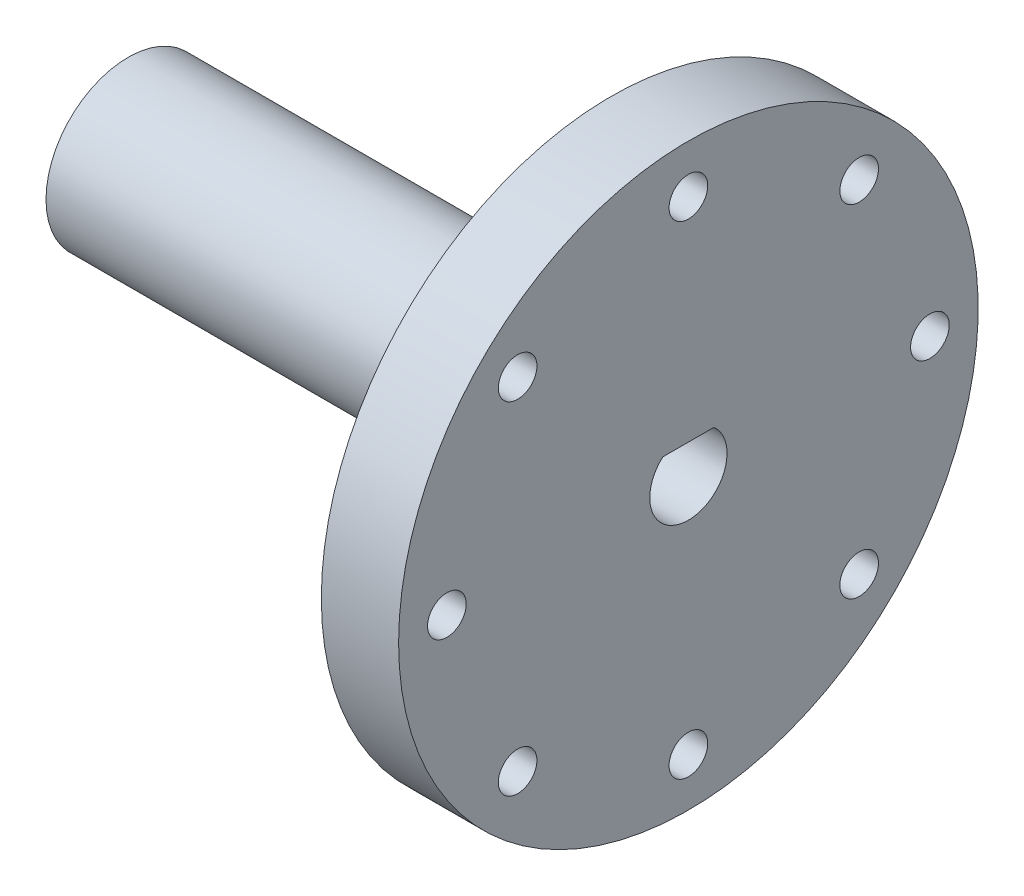
SolidWorks part; units mm, degrees
ref_plane "Front Plane" through (0, 0, 0) normal (0, 0, 1) x (1, 0, 0)
ref_plane "Top Plane" through (0, 0, 0) normal (0, 1, 0) x (1, 0, 0)
ref_plane "Right Plane" through (0, 0, 0) normal (1, 0, 0) x (0, 0, -1)
sketch "Sketch1" plane through (0, 0, 0) normal (0, 0, 1) x (1, 0, 0)
  line L0 (0, 4) -> (58, 4)
  line L1 (58, 4) -> (58, 30)
  line L2 (58, 30) -> (50, 30)
  line L3 (50, 30) -> (50, 8.5)
  line L4 (50, 8.5) -> (0, 8.5)
  line L5 (0, 8.5) -> (0, 4)
  line L6 (0, 0) -> (73.8575, 0) construction
  dimension "D1" = 58
  dimension "D2" = 50
  dimension "D3" = 4
  dimension "D4" = 8.5
  dimension "D5" = 30
revolve "Revolve1" add sketch "Sketch1" angle 360 about L6
sketch "Sketch2" plane through (50, 0, 0) normal (-1, 0, 0) x (0, 0, 1)
  circle A0 centre (0, 25) radius 2
  circle A1 centre (17.6777, 17.6777) radius 2
  circle A2 centre (25, 0) radius 2
  circle A3 centre (17.6777, -17.6777) radius 2
  circle A4 centre (0, -25) radius 2
  circle A5 centre (-17.6777, -17.6777) radius 2
  circle A6 centre (-25, 0) radius 2
  circle A7 centre (-17.6777, 17.6777) radius 2
  point P20 (0, 0)
  dimension "D2" = 4
  dimension "D1" = 25
  dimension "D3" = 8
extrude "Cut-Extrude1" cut sketch "Sketch2" against normal blind 10
sketch "Sketch3" plane through (0, 0, 0) normal (-1, 0, 0) x (0, 0, 1)
  line L0 (-2.6458, 3) -> (2.6458, 3)
  circle A0 centre (0, 0) radius 4 construction
  arc A1 (2.6458, 3) -> (-2.6458, 3) centre (0, 0) ccw
  dimension "D1" = 3
extrude "Boss-Extrude1" add sketch "Sketch3" against normal through all
sketch "Sketch4" plane through (50, 0, 0) normal (-1, 0, 0) x (0, 0, 1)
  line L0 (-2.6458, 3) -> (2.6458, 3) construction
  line L1 (-2.6458, 3) -> (2.6458, 3)
  circle A1 centre (0, 0) radius 10
  arc A2 (-2.6458, 3) -> (2.6458, 3) centre (0, 0) ccw construction
  arc A3 (-2.6458, 3) -> (2.6458, 3) centre (0, 0) ccw
  dimension "D2" = 20
extrude "Boss-Extrude2" add sketch "Sketch4" along normal blind 11
